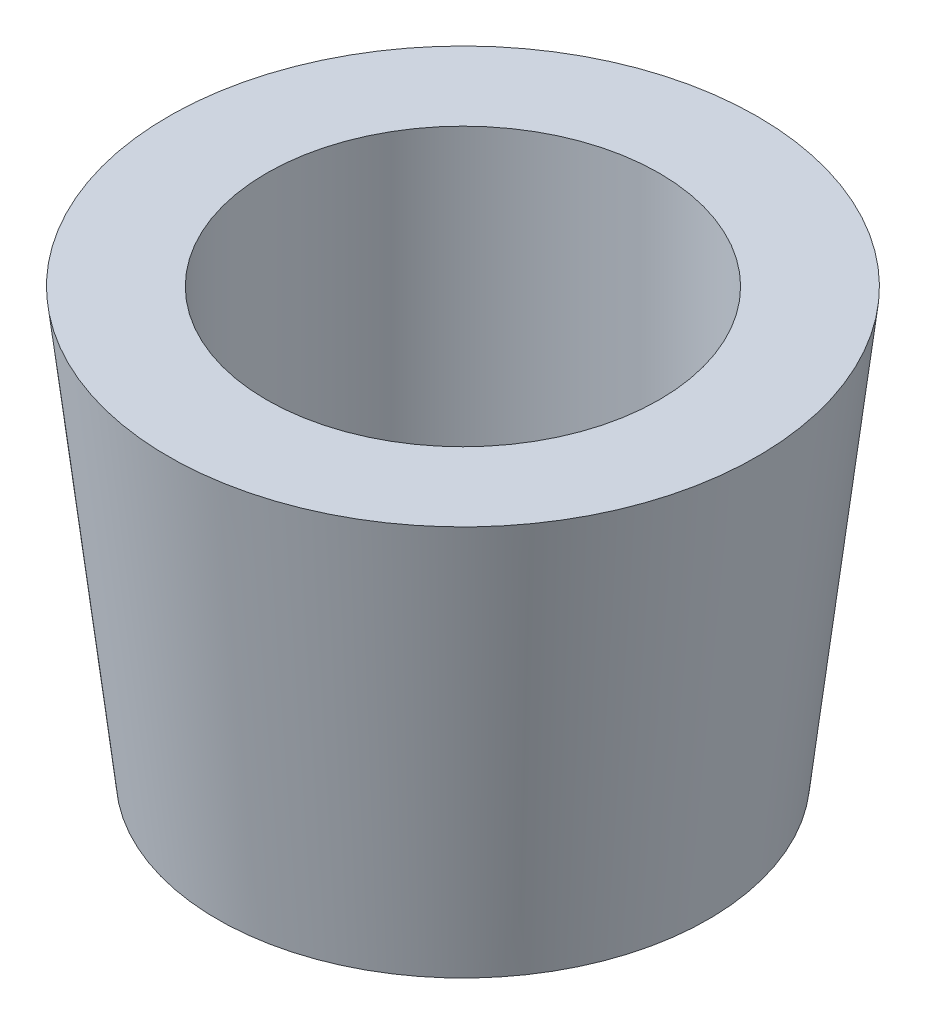
SolidWorks part; units mm, degrees
material "Silicon Rubber"
ref_plane "Front Plane" through (0, 0, 0) normal (0, 0, 1) x (1, 0, 0)
ref_plane "Top Plane" through (0, 0, 0) normal (0, 1, 0) x (1, 0, 0)
ref_plane "Right Plane" through (0, 0, 0) normal (1, 0, 0) x (0, 0, -1)
sketch "Sketch1" plane through (0, 0, 0) normal (0, 0, 1) x (1, 0, 0)
  line L0 (3, 3.25) -> (4.5, 3.25)
  line L1 (4.5, 3.25) -> (3.75, -3.25)
  line L2 (3.75, -3.25) -> (3, -3.25)
  line L3 (3, -3.25) -> (3, 3.25)
  line L4 (0, 0) -> (3, 0) construction
  line L5 (0, 0) -> (0, 3.25) construction
  dimension "InnerDia" = 6
  dimension "TopOuterDiaControl" = 1.5
  dimension "BottomOuterDiaControl" = 0.75
  dimension "Height" = 6.5
  dimension "RefOuterDia" = 9
  dimension "RefBottomOuterDia" = 7.5
revolve "Revolve1" add sketch "Sketch1" angle 360 about L5
